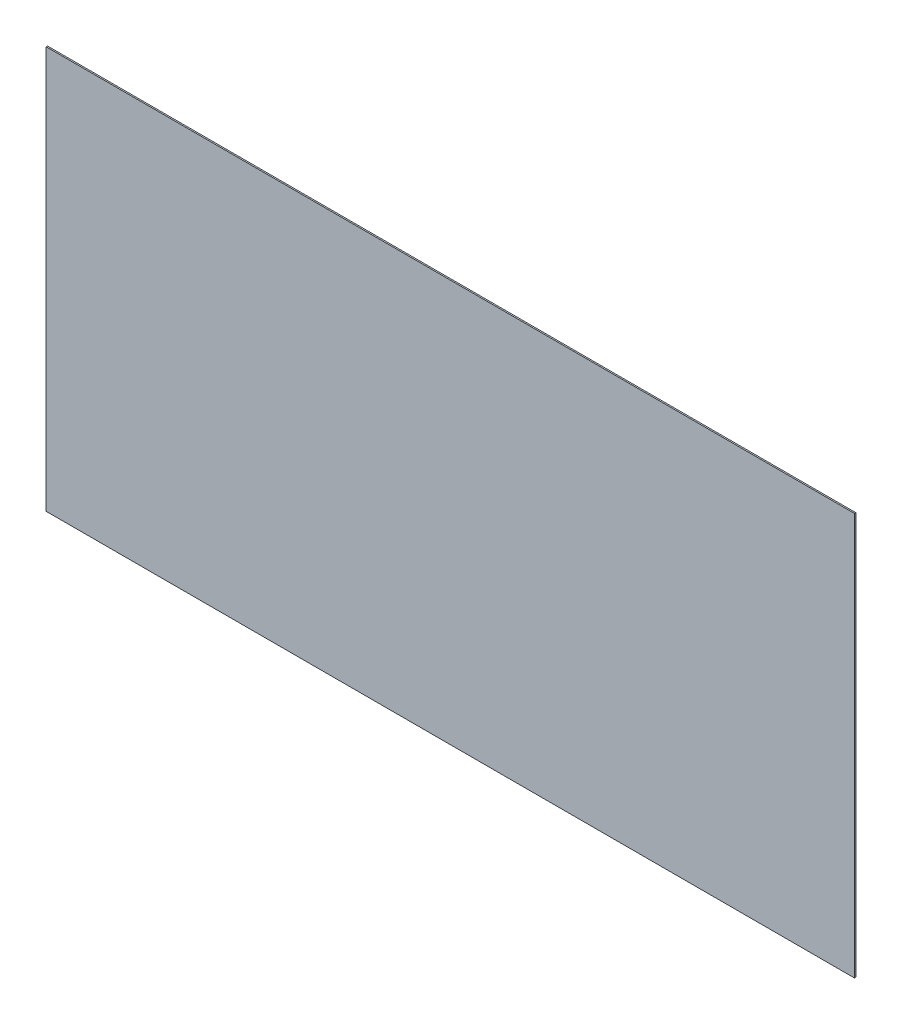
SolidWorks part; units mm, degrees
ref_plane "Front Plane" through (0, 0, 0) normal (0, 0, 1) x (1, 0, 0)
ref_plane "Top Plane" through (0, 0, 0) normal (0, 1, 0) x (1, 0, 0)
ref_plane "Right Plane" through (0, 0, 0) normal (1, 0, 0) x (0, 0, -1)
other "Configuration Table"
sketch "Sketch1" plane through (0, 0, 0) normal (0, 0, 1) x (1, 0, 0)
  line L1 (13.7, 4) -> (604.3, 4)
  line L2 (13.7, 4) -> (13.7, 298)
  line L3 (13.7, 298) -> (604.3, 298)
  line L4 (604.3, 4) -> (604.3, 298)
extrude "CEK_1L_kutu_arka_1.0_1" add sketch "Sketch1" against normal blind 1 from offset 699 separate body
